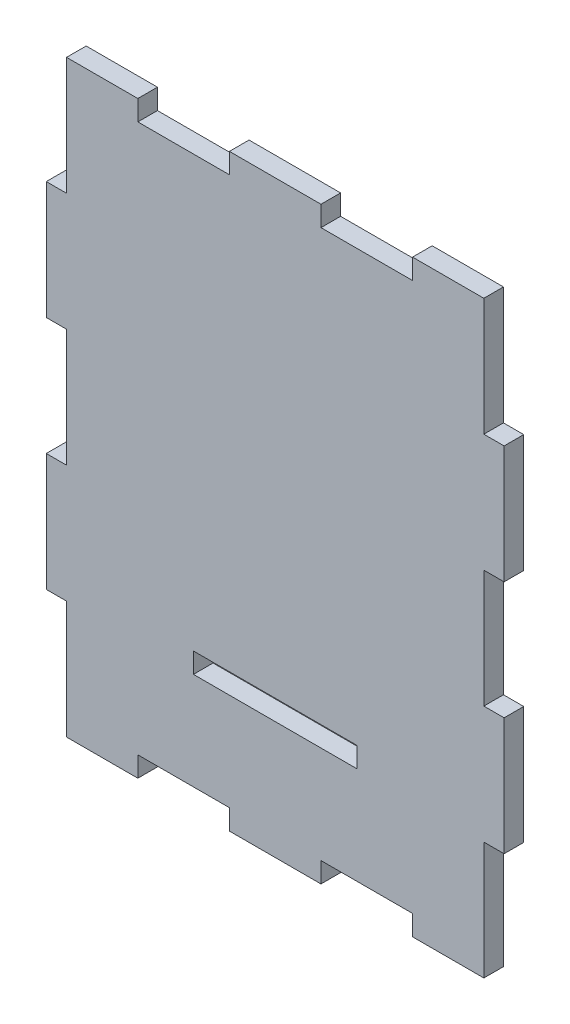
SolidWorks part; units mm, degrees
ref_plane "Alzado" through (0, 0, 0) normal (0, 0, 1) x (1, 0, 0)
ref_plane "Planta" through (0, 0, 0) normal (0, 1, 0) x (1, 0, 0)
ref_plane "Vista lateral" through (0, 0, 0) normal (1, 0, 0) x (0, 0, -1)
sketch "Croquis1" plane through (0, 0, 0) normal (0, 0, 1) x (1, 0, 0)
  line L0 (0, 45) -> (0, -45) construction
  line L1 (-35, -45) -> (35, -45)
  line L2 (-35, -45) -> (-35, 45)
  line L3 (-35, 45) -> (35, 45)
  line L4 (35, -45) -> (35, 45)
  line L5 (-35, -45) -> (35, 45) construction
  line L6 (-35, 45) -> (35, -45) construction
  line L7 (-35, 45) -> (-31.9, 45)
  line L8 (-35, 45) -> (-35, 27)
  line L9 (-35, 27) -> (-31.9, 27)
  line L10 (-31.9, 45) -> (-31.9, 27)
  line L11 (-35, -45) -> (-31.9, -45)
  line L12 (-35, -45) -> (-35, -27)
  line L13 (-35, -27) -> (-31.9, -27)
  line L14 (-31.9, -45) -> (-31.9, -27)
  line L15 (-35, 9) -> (-31.9, 9)
  line L16 (-35, 9) -> (-35, -9)
  line L17 (-35, -9) -> (-31.9, -9)
  line L18 (-31.9, 9) -> (-31.9, -9)
  line L19 (21, 45) -> (7, 45)
  line L20 (21, 45) -> (21, 41.9)
  line L21 (21, 41.9) -> (7, 41.9)
  line L22 (7, 45) -> (7, 41.9)
  line L23 (-21, 45) -> (-7, 45)
  line L24 (-21, 45) -> (-21, 41.9)
  line L25 (-21, 41.9) -> (-7, 41.9)
  line L26 (-7, 45) -> (-7, 41.9)
  line L27 (35, -27) -> (31.9, -27)
  line L28 (31.9, -45) -> (31.9, -27)
  line L29 (35, -45) -> (31.9, -45)
  line L30 (35, -45) -> (35, -27)
  line L31 (35, -9) -> (31.9, -9)
  line L32 (31.9, 9) -> (31.9, -9)
  line L33 (35, 9) -> (31.9, 9)
  line L34 (35, 9) -> (35, -9)
  line L35 (35, 27) -> (31.9, 27)
  line L36 (31.9, 45) -> (31.9, 27)
  line L37 (35, 45) -> (31.9, 45)
  line L38 (35, 45) -> (35, 27)
  line L39 (53.9536, 0) -> (-65.8161, 0) construction
  line L40 (21, -45) -> (21, -41.9)
  line L41 (21, -41.9) -> (7, -41.9)
  line L42 (7, -45) -> (7, -41.9)
  line L43 (-7, -45) -> (-7, -41.9)
  line L44 (-21, -41.9) -> (-7, -41.9)
  line L45 (-21, -45) -> (-21, -41.9)
  point P0 (0, 0)
  dimension "D1" = 70
  dimension "D2" = 90
  dimension "D3" = 18
  dimension "D4" = 18
  dimension "D5" = 18
  dimension "D6" = 18
  dimension "D7" = 3.1
  dimension "D8" = 14
  dimension "D9" = 14
  dimension "D10" = 14
  dimension "D11" = 14
  dimension "D12" = 3.1
extrude "Saliente-Extruir1" add sketch "Croquis1" along normal mid plane 3 contours L36 L3 L20 L21 L22 L26 L25 L24 L10 L9 L2 L15 L18 L17 L13 L14 L1 L28 L27 L4 L31 L32 L33 L35
sketch "Croquis2" plane through (0, 0, -1.5) normal (0, 0, -1) x (-1, 0, 0)
  line L0 (0, 45) -> (0, -45) construction
  line L1 (7, 45) -> (-7, 45) construction
  line L2 (31.9, -45) -> (21, -45) construction
  line L4 (-12.5, -23.9) -> (12.5, -23.9)
  line L5 (-12.5, -23.9) -> (-12.5, -27)
  line L6 (-12.5, -27) -> (12.5, -27)
  line L7 (12.5, -23.9) -> (12.5, -27)
  point P10 (0, -23.9)
  point P11 (0, 0)
  dimension "D1" = 18
  dimension "D2" = 3.1
  dimension "D3" = 25
extrude "Cortar-Extruir1" cut sketch "Croquis2" against normal blind 10
